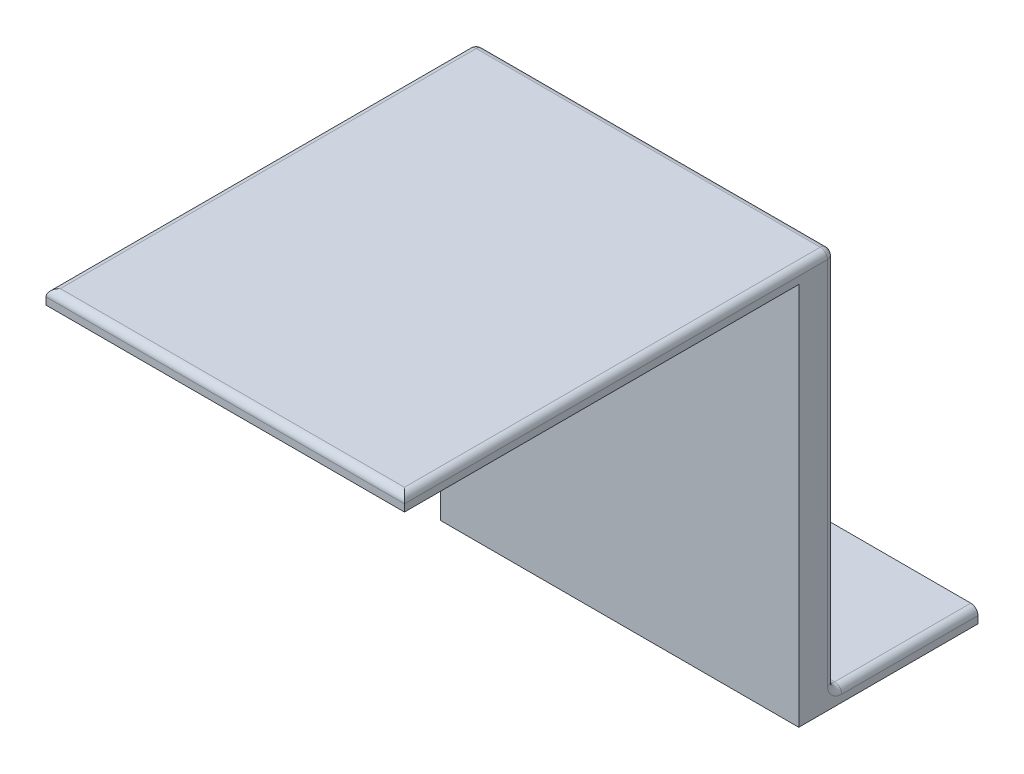
SolidWorks part; units mm, degrees
ref_plane "前视基准面" through (0, 0, 0) normal (0, 0, 1) x (1, 0, 0)
ref_plane "上视基准面" through (0, 0, 0) normal (0, 1, 0) x (1, 0, 0)
ref_plane "右视基准面" through (0, 0, 0) normal (1, 0, 0) x (0, 0, -1)
sketch "草图1" plane through (0, 0, 0) normal (0, 0, 1) x (1, 0, 0)
  line L1 (-18.1818, 18.568) -> (31.8182, 18.568)
  line L2 (-18.1818, 18.568) -> (-18.1818, -36.932)
  line L3 (-18.1818, -36.932) -> (31.8182, -36.932)
  line L4 (31.8182, 18.568) -> (31.8182, -36.932)
  dimension "D1" = 50
  dimension "D2" = 55.5
extrude "凸台-拉伸1" add sketch "草图1" along normal blind 60
sketch "草图3" plane through (0, 0, 60) normal (0, 0, 1) x (1, 0, 0)
  line L0 (-18.1818, 18.568) -> (-18.1818, -36.932) construction
  line L1 (31.8182, -36.932) -> (-18.1818, -36.932)
  line L2 (31.8182, -36.932) -> (31.8182, 16.568)
  line L3 (31.8182, 16.568) -> (-18.1818, 16.568)
  line L4 (-18.1818, -36.932) -> (-18.1818, 16.568)
extrude "切除-拉伸1" cut sketch "草图3" against normal blind 55
sketch "草图4" plane through (0, 0, 0) normal (0, 0, -1) x (-1, 0, 0)
  line L0 (-31.8182, -36.932) -> (-31.8182, 18.568) construction
  line L1 (18.1818, -36.932) -> (-31.8182, -36.932)
  line L2 (18.1818, -36.932) -> (18.1818, -34.932)
  line L3 (18.1818, -34.932) -> (-31.8182, -34.932)
  line L4 (-31.8182, -36.932) -> (-31.8182, -34.932)
extrude "凸台-拉伸2" add sketch "草图4" along normal blind 20
fillet "圆角5" radius 1 9 edges at (31.8182, -34.932, -10) (-18.1818, -34.932, -10) (31.8182, -8.182, 0) (-18.1818, -8.182, 0) (6.8182, -34.932, 0) (31.8182, 18.568, 30) (6.8182, 18.568, 60) (-18.1818, 18.568, 30) (6.8182, 18.568, 0)
scale "缩放比例1" scale about origin uniform scaling yes scale factor 1.7
